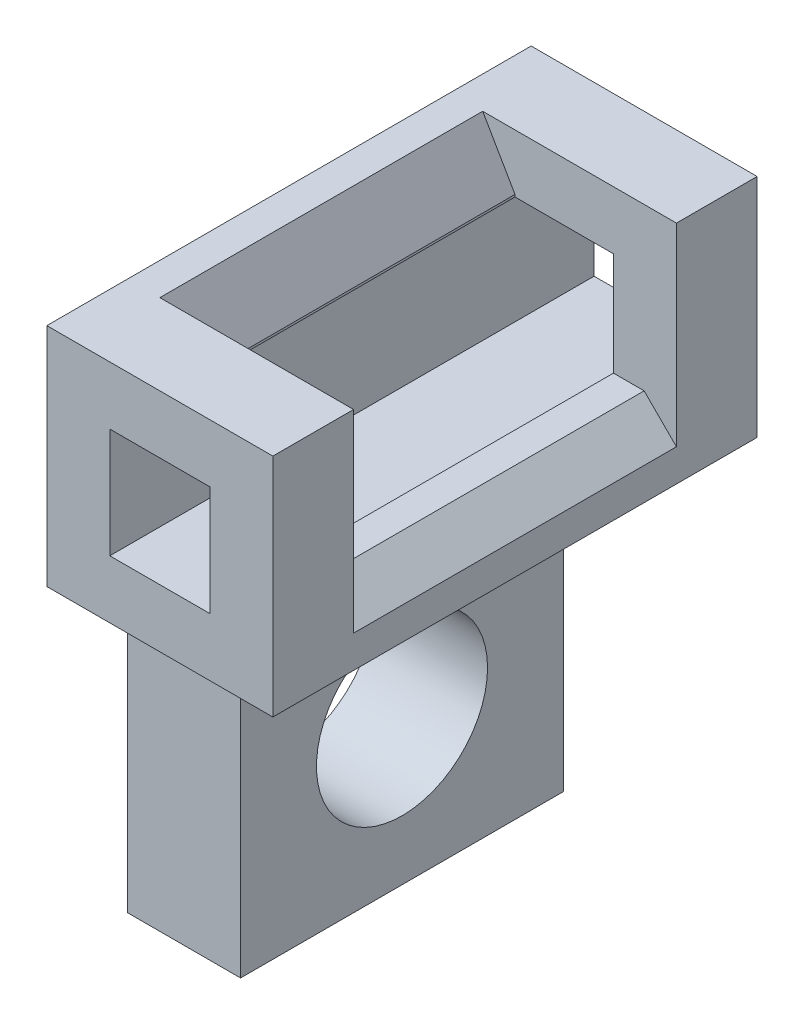
SolidWorks part; units mm, degrees
ref_plane "Ebene vorne" through (0, 0, 0) normal (0, 0, 1) x (1, 0, 0)
ref_plane "Ebene oben" through (0, 0, 0) normal (0, 1, 0) x (1, 0, 0)
ref_plane "Ebene rechts" through (0, 0, 0) normal (1, 0, 0) x (0, 0, -1)
sketch "Skizze1" plane through (0, 0, 0) normal (0, 0, 1) x (1, 0, 0)
  line L1 (-3.5, 3.5) -> (3.5, 3.5)
  line L2 (-3.5, 3.5) -> (-3.5, -3.5)
  line L3 (-3.5, -3.5) -> (3.5, -3.5)
  line L4 (3.5, 3.5) -> (3.5, -3.5)
  line L5 (-3.5, 3.5) -> (3.5, -3.5) construction
  line L6 (-3.5, -3.5) -> (3.5, 3.5) construction
  point P0 (0, 0)
  dimension "D1" = 7
  dimension "D2" = 7
extrude "Aufsatz-Linear austragen1" add sketch "Skizze1" along normal blind 15
sketch "Skizze2" plane through (0, 0, 15) normal (0, 0, 1) x (1, 0, 0)
  line L1 (-1.55, 1.7) -> (1.55, 1.7)
  line L2 (-1.55, 1.7) -> (-1.55, -1.7)
  line L3 (-1.55, -1.7) -> (1.55, -1.7)
  line L4 (1.55, 1.7) -> (1.55, -1.7)
  line L5 (-1.55, 1.7) -> (1.55, -1.7) construction
  line L6 (-1.55, -1.7) -> (1.55, 1.7) construction
  point P0 (0, 0)
  dimension "D1" = 3.4
  dimension "D2" = 3.1
extrude "Schnitt-Linear austragen1" cut sketch "Skizze2" against normal through all
sketch "Skizze3" plane through (0, 3.5, 0) normal (0, 1, 0) x (1, 0, 0)
  line L1 (-1.5, -2.5) -> (3.5, -2.5)
  line L2 (-1.5, -2.5) -> (-1.5, -12.5)
  line L3 (-1.5, -12.5) -> (3.5, -12.5)
  line L4 (3.5, -2.5) -> (3.5, -12.5)
  line L5 (-1.5, -2.5) -> (3.5, -12.5) construction
  line L6 (-1.5, -12.5) -> (3.5, -2.5) construction
  line L7 (3.5, -15) -> (3.5, 0) construction
  line L8 (3.5, -15) -> (-3.5, -15) construction
  point P0 (1, -7.5)
  dimension "D1" = 2.5
  dimension "D2" = 0
  dimension "D3" = 7.5
  dimension "D4" = 10
extrude "Schnitt-Linear austragen2" cut sketch "Skizze3" against normal blind 5
chamfer "Fase2" distance 1 angle 60 1 edges at (-1.5, 3.5, 7.5)
sketch "Skizze4" plane through (3.5, 0, 0) normal (1, 0, 0) x (0, 0, -1)
  line L0 (-15, -3.5) -> (0, -3.5) construction
  line L1 (-12.5, -3.5) -> (-2.5, -3.5)
  line L2 (-12.5, -3.5) -> (-12.5, 0)
  line L3 (-12.5, 0) -> (-2.5, 0)
  line L4 (-2.5, -3.5) -> (-2.5, 0)
  line L5 (-15, -3.5) -> (-15, 3.5) construction
  line L6 (0, -3.5) -> (0, 3.5) construction
  dimension "D1" = 2.5
  dimension "D2" = 2.5
  dimension "D3" = 3.5
sketch "Skizze5" plane through (0, -3.5, 0) normal (0, -1, 0) x (1, 0, 0)
  line L0 (-3.5, 15) -> (-3.5, 0) construction
  line L1 (-3.5, 12.5) -> (0, 12.5)
  line L2 (-3.5, 12.5) -> (-3.5, 2.5)
  line L3 (-3.5, 2.5) -> (0, 2.5)
  line L4 (0, 12.5) -> (0, 2.5)
  line L5 (-3.5, 15) -> (3.5, 15) construction
  line L6 (-3.5, 0) -> (3.5, 0) construction
  dimension "D1" = 2.5
  dimension "D2" = 2.5
  dimension "D3" = 3.5
extrude "Aufsatz-Linear austragen2" add sketch "Skizze5" along normal blind 10
chamfer "Fase3" distance 1 angle 45 3 edges at (-1.75, -3.5, 2.5) (0, -3.5, 7.5) (-1.75, -3.5, 12.5)
sketch "Skizze6" plane through (0, 0, 0) normal (1, 0, 0) x (0, 0, -1)
  line L0 (-12.5, -13.5) -> (-12.5, -4.5) construction
  line L1 (-2.5, -13.5) -> (-12.5, -13.5) construction
  circle A0 centre (-7.5, -9) radius 2.65
  dimension "D3" = 5.3
  dimension "D1" = 5
  dimension "D2" = 4.5
extrude "Schnitt-Linear austragen3" cut sketch "Skizze6" against normal blind 10
chamfer "Fase4" distance 1 angle 45 1 edges at (3.5, -1.5, 7.5)
